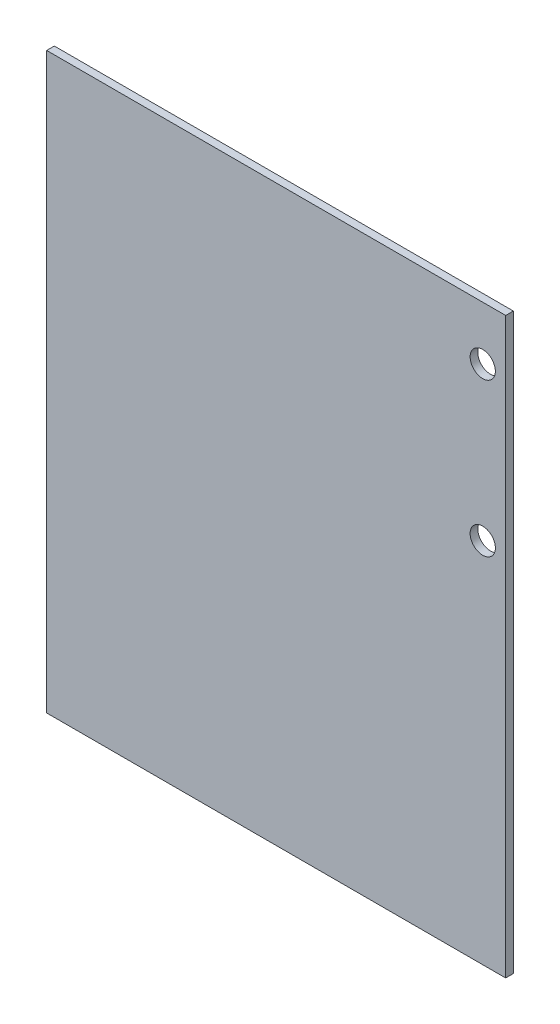
SolidWorks part; units mm, degrees
material "环氧板"
ref_plane "前视基准面" through (0, 0, 0) normal (0, 0, 1) x (1, 0, 0)
ref_plane "上视基准面" through (0, 0, 0) normal (0, 1, 0) x (1, 0, 0)
ref_plane "右视基准面" through (0, 0, 0) normal (1, 0, 0) x (0, 0, -1)
other "Configuration Table"
sketch "草图1" plane through (0, 0, 0) normal (0, 0, 1) x (1, 0, 0)
  line L1 (-30, 37.5) -> (30, 37.5)
  line L2 (-30, 37.5) -> (-30, -37.5)
  line L3 (-30, -37.5) -> (30, -37.5)
  line L4 (30, 37.5) -> (30, -37.5)
  line L5 (-30, 37.5) -> (30, -37.5) construction
  line L6 (-30, -37.5) -> (30, 37.5) construction
  point P0 (0, 0)
  dimension "D1" = 75
  dimension "D2" = 60
extrude "凸台-拉伸1" add sketch "草图1" along normal blind 1
sketch "草图3" plane through (0, 0, 1) normal (0, 0, 1) x (1, 0, 0)
  line L0 (30, 37.5) -> (-30, 37.5) construction
  line L1 (30, -37.5) -> (30, 37.5) construction
  circle A0 centre (27, 30.5) radius 1.65
  circle A1 centre (27, 10.5) radius 1.65
  point P6 (0, 0)
  point P9 (27, -7.3089)
  dimension "D1" = 7
  dimension "D2" = 3.3
  dimension "D4" = 20
  dimension "D3" = 3
extrude "切除-拉伸1" cut sketch "草图3" against normal through all
